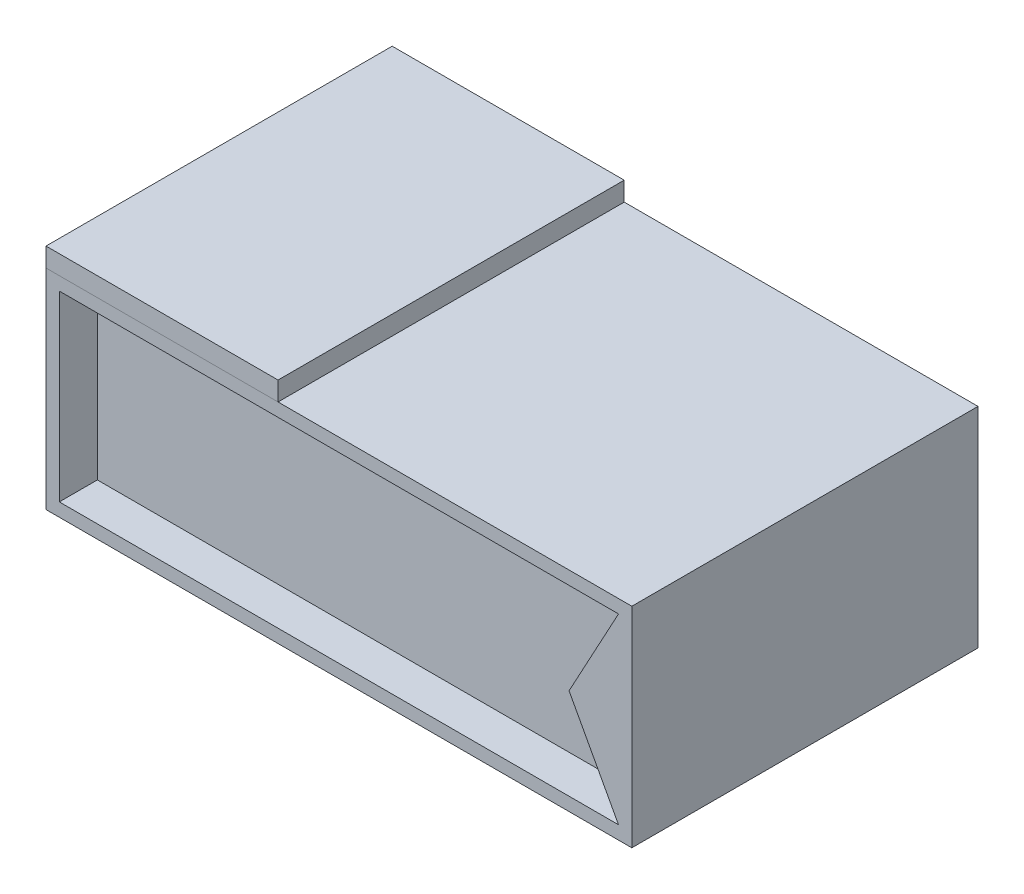
SolidWorks part; units mm, degrees
ref_plane "Plan de face" through (0, 0, 0) normal (0, 0, 1) x (1, 0, 0)
ref_plane "Plan de dessus" through (0, 0, 0) normal (0, 1, 0) x (1, 0, 0)
ref_plane "Plan de droite" through (0, 0, 0) normal (1, 0, 0) x (0, 0, -1)
sketch "Esquisse1" plane through (0, 0, 0) normal (1, 0, 0) x (0, 0, -1)
  line L1 (-45.5, 27.5) -> (45.5, 27.5)
  line L2 (-45.5, 27.5) -> (-45.5, -27.5)
  line L3 (-45.5, -27.5) -> (45.5, -27.5)
  line L4 (45.5, 27.5) -> (45.5, -27.5)
  point P4 (0, 27.5)
  point P6 (-45.5, 0)
  dimension "D1" = 91
  dimension "D2" = 55
extrude "Boss.-Extru.1" add sketch "Esquisse1" along normal mid plane 154
sketch "Esquisse3" plane through (0, 27.5, 0) normal (0, 1, 0) x (1, 0, 0)
  line L1 (-77, 45.5) -> (-16, 45.5)
  line L2 (-77, 45.5) -> (-77, -45.5)
  line L3 (-77, -45.5) -> (-16, -45.5)
  line L4 (-16, 45.5) -> (-16, -45.5)
  line L5 (77, -45.5) -> (-77, -45.5) construction
  dimension "D1" = 61
extrude "Boss.-Extru.2" add sketch "Esquisse3" along normal blind 5 separate body
sketch "Esquisse4" plane through (0, 0, 45.5) normal (0, 0, 1) x (1, 0, 0)
  line L0 (77, 27.5) -> (-77, 27.5) construction
  line L1 (-73.5, 24) -> (73.5, 24)
  line L2 (-73.5, 24) -> (-73.5, -24)
  line L3 (-73.5, -24) -> (73.5, -24)
  line L4 (73.5, 24) -> (73.5, -24) construction
  line L5 (-77, 27.5) -> (-77, -27.5) construction
  line L6 (73.5, -24) -> (60.5, 0)
  line L7 (60.5, 0) -> (73.5, 24)
  point P4 (0, 24)
  point P6 (-73.5, 0)
  dimension "D1" = 3.5
  dimension "D2" = 3.5
  dimension "D3" = 13
extrude "Enlèv. mat.-Extru.1" cut sketch "Esquisse4" against normal blind 10
mirror "Symétrie1" about plane through (0, 0, 0) normal (0, 0, 1) of "Enlèv. mat.-Extru.1"
equation "\"D2@Esquisse4\"=\"D1@Esquisse4\""
